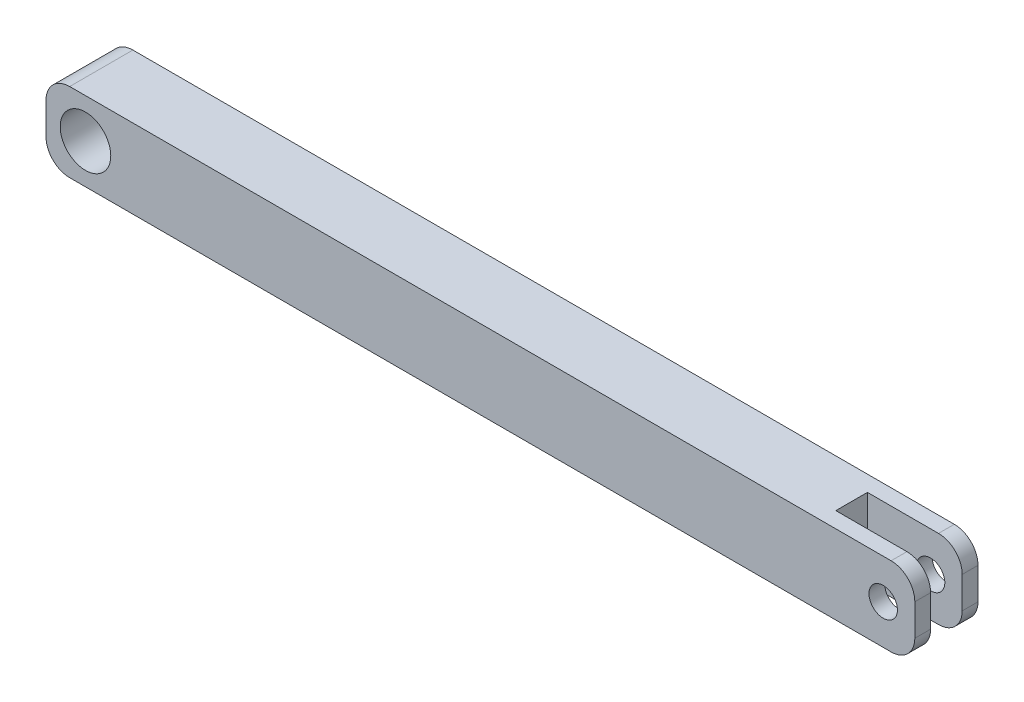
SolidWorks part; units mm, degrees
ref_plane "前视基准面" through (0, 0, 0) normal (0, 0, 1) x (1, 0, 0)
ref_plane "上视基准面" through (0, 0, 0) normal (0, 1, 0) x (1, 0, 0)
ref_plane "右视基准面" through (0, 0, 0) normal (1, 0, 0) x (0, 0, -1)
other "Configuration Table"
sketch "草图5" plane through (0, 0, 0) normal (0, 1, 0) x (1, 0, 0)
  line L0 (0, 0) -> (0, -3)
  line L4 (55, -3) -> (55, 0)
  line L8 (55, 0) -> (0, 0)
  line L9 (0, -3) -> (55, -3)
  dimension "D6" = 3
  dimension "D1" = 55
  dimension "D5" = 3
extrude "凸台-拉伸1" add sketch "草图5" along normal blind 5
sketch "草图6" plane through (0, 0, 3) normal (0, 0, 1) x (1, 0, 0)
  line L2 (0, 5) -> (0, 0) construction
  line L3 (0, 5) -> (55, 5) construction
  circle A0 centre (2.5, 2.5) radius 1.6
  dimension "D1" = 3.2
  dimension "D2" = 2.5
  dimension "D3" = 2.5
extrude "切除-拉伸1" cut sketch "草图6" against normal up to next
sketch "草图7" plane through (0, 0, 0) normal (0, 0, 1) x (1, 0, 0)
  line L0 (55, 5) -> (55, 0) construction
  circle A0 centre (53, 2.5) radius 0.9
  point P6 (55, 2.5)
  dimension "D1" = 1.8
  dimension "D2" = 2
extrude "切除-拉伸2" cut sketch "草图7" along normal up to next
fillet "圆角1" radius 1.5 4 edges at (55, 5, 1.5) (55, 0, 1.5) (0, 0, 1.5) (0, 5, 1.5)
sketch "草图8" plane through (0, 5, 0) normal (0, 1, 0) x (1, 0, 0)
  line L0 (55, 0) -> (55, -3) construction
  line L1 (55, -0.7) -> (49, -0.7)
  line L2 (55, -0.7) -> (55, -2.3)
  line L3 (55, -2.3) -> (49, -2.3)
  line L4 (49, -0.7) -> (49, -2.3)
  point P6 (55, -1.5)
  dimension "D1" = 1.6
  dimension "D2" = 6
extrude "切除-拉伸3" cut sketch "草图8" against normal blind 10
sketch "草图10" plane through (0, 0, 3) normal (0, 0, 1) x (1, 0, 0)
  line L3 (55, 1.5) -> (55, 3.5)
  line L6 (0, 3.5) -> (0, 1.5)
  line L10 (0, 3.5) -> (0, 1.5)
  line L13 (55, 1.5) -> (55, 3.5)
  line L18 (53.5, 5) -> (1.5, 5)
  line L19 (53.5, 5) -> (1.5, 5)
  line L20 (1.5, 0) -> (53.5, 0)
  line L21 (1.5, 0) -> (53.5, 0)
  circle A0 centre (2.5, 2.5) radius 1.6 construction
  circle A1 centre (2.5, 2.5) radius 1.6
  circle A2 centre (53, 2.5) radius 0.9 construction
  circle A3 centre (53, 2.5) radius 0.9
  arc A4 (55, 3.5) -> (53.5, 5) centre (53.5, 3.5) ccw
  arc A5 (1.5, 5) -> (0, 3.5) centre (1.5, 3.5) ccw
  arc A6 (0, 1.5) -> (1.5, 0) centre (1.5, 1.5) ccw
  arc A9 (1.5, 5) -> (0, 3.5) centre (1.5, 3.5) ccw
  arc A10 (0, 1.5) -> (1.5, 0) centre (1.5, 1.5) ccw
  arc A19 (55, 3.5) -> (53.5, 5) centre (53.5, 3.5) ccw
  arc A20 (53.5, 0) -> (55, 1.5) centre (53.5, 1.5) ccw
  arc A21 (53.5, 0) -> (55, 1.5) centre (53.5, 1.5) ccw
  dimension "D1" = 0
extrude "凸台-拉伸2" add sketch "草图10" along normal blind 0.5
sketch "草图11" plane through (0, 0, 0) normal (0, 0, -1) x (-1, 0, 0)
  line L4 (-1.5, 5) -> (-53.5, 5)
  line L5 (-55, 3.5) -> (-55, 1.5)
  line L6 (-53.5, 0) -> (-1.5, 0)
  line L7 (0, 1.5) -> (0, 3.5)
  line L8 (-1.5, 5) -> (-53.5, 5)
  line L9 (-55, 3.5) -> (-55, 1.5)
  line L10 (-53.5, 0) -> (-1.5, 0)
  line L11 (0, 1.5) -> (0, 3.5)
  circle A0 centre (-53, 2.5) radius 0.9 construction
  circle A1 centre (-2.5, 2.5) radius 1.6 construction
  circle A2 centre (-53, 2.5) radius 0.9
  circle A3 centre (-2.5, 2.5) radius 1.6
  arc A4 (-53.5, 5) -> (-55, 3.5) centre (-53.5, 3.5) ccw
  arc A5 (-55, 1.5) -> (-53.5, 0) centre (-53.5, 1.5) ccw
  arc A6 (-1.5, 0) -> (0, 1.5) centre (-1.5, 1.5) ccw
  arc A7 (0, 3.5) -> (-1.5, 5) centre (-1.5, 3.5) ccw
  arc A8 (-53.5, 5) -> (-55, 3.5) centre (-53.5, 3.5) ccw
  arc A9 (-55, 1.5) -> (-53.5, 0) centre (-53.5, 1.5) ccw
  arc A10 (-1.5, 0) -> (0, 1.5) centre (-1.5, 1.5) ccw
  arc A11 (0, 3.5) -> (-1.5, 5) centre (-1.5, 3.5) ccw
  dimension "D1" = 0
extrude "凸台-拉伸3" add sketch "草图11" along normal blind 0.5
sketch "草图12" plane through (0, 5, 0) normal (0, 1, 0) x (1, 0, 0)
  line L0 (53.5, -0.7) -> (49, -0.7) construction
  line L1 (55.1416, -2.5) -> (49, -2.5)
  line L2 (55.1416, -2.5) -> (55.1416, -0.5)
  line L3 (55.1416, -0.5) -> (49, -0.5)
  line L4 (49, -2.5) -> (49, -0.5)
  line L5 (55.1416, -2.5) -> (49, -0.5) construction
  line L6 (55.1416, -0.5) -> (49, -2.5) construction
  line L7 (49, -2.3) -> (53.5, -2.3) construction
  point P0 (52.0708, -1.5)
  dimension "D1" = 0.2
  dimension "D2" = 0.2
extrude "切除-拉伸4" cut sketch "草图12" against normal blind 10
